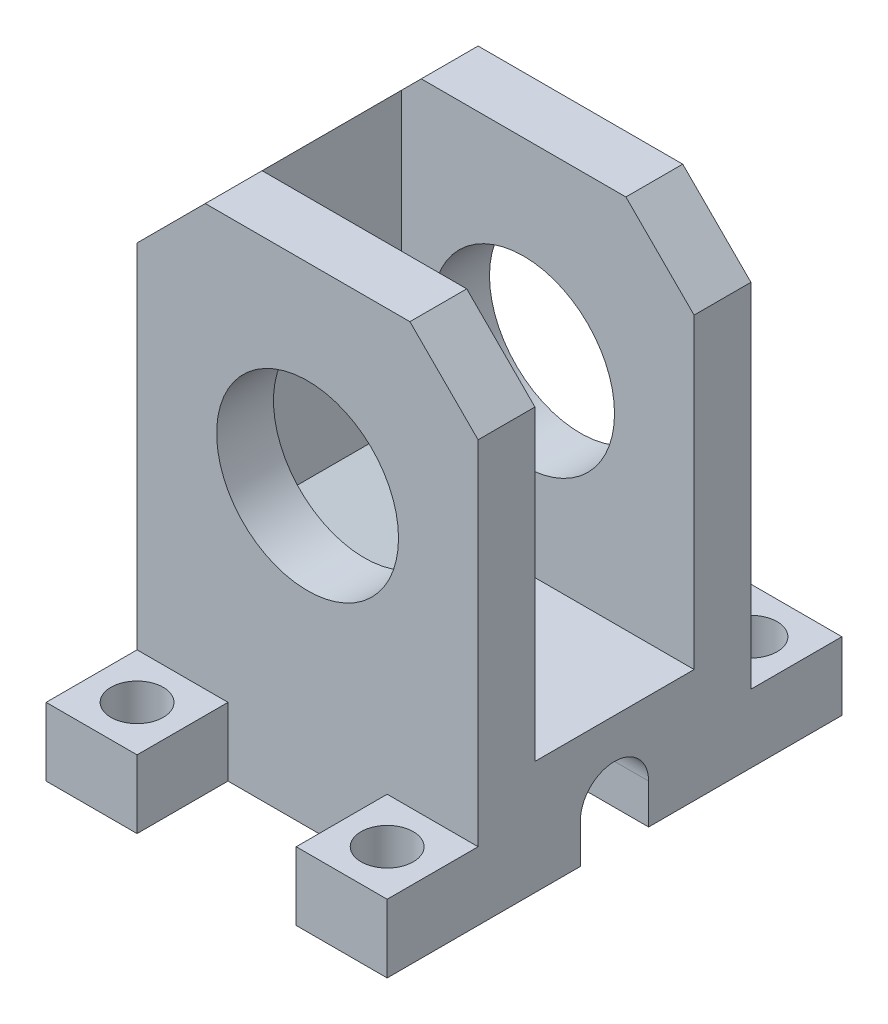
SolidWorks part; units mm, degrees
ref_plane "Plan de face" through (0, 0, 0) normal (0, 0, 1) x (1, 0, 0)
ref_plane "Plan de dessus" through (0, 0, 0) normal (0, 1, 0) x (1, 0, 0)
ref_plane "Plan de droite" through (0, 0, 0) normal (1, 0, 0) x (0, 0, -1)
sketch "Esquisse1" plane through (0, 0, 0) normal (0, 0, 1) x (1, 0, 0)
  line L0 (0, 0) -> (15, 0)
  line L1 (0, 0) -> (-15, 0)
  line L2 (-15, 0) -> (-15, 45)
  line L3 (-15, 45) -> (15, 45)
  line L4 (15, 45) -> (15, 0)
  line L5 (0, 0) -> (0, 28) construction
  circle A0 centre (0, 28) radius 8
  dimension "D1" = 28
extrude "Boss.-Extru.1" add sketch "Esquisse1" against normal blind 5
sketch "Esquisse2" plane through (0, 0, -5) normal (0, 0, -1) x (-1, 0, 0)
  line L0 (-15, 0) -> (15, 0)
  line L1 (15, 0) -> (15, 12)
  line L2 (15, 45) -> (15, 0) construction
  line L3 (15, 12) -> (-15, 12)
  line L4 (-15, 0) -> (-15, 45) construction
  line L5 (-15, 12) -> (-15, 0)
extrude "Boss.-Extru.2" add sketch "Esquisse2" along normal blind 14
sketch "Esquisse4" plane through (0, 0, 0) normal (0, -1, 0) x (1, 0, 0)
  line L0 (-15, -19) -> (15, -19)
  line L1 (15, -19) -> (15, -24)
  line L2 (15, -24) -> (-15, -24)
  line L3 (-15, -24) -> (-15, -19)
extrude "Boss.-Extru.3" add sketch "Esquisse4" against normal blind 45
sketch "Esquisse6" plane through (0, 0, -24) normal (0, 0, -1) x (-1, 0, 0)
  line L0 (0, 0) -> (0, 28) construction
  circle A1 centre (0, 28) radius 8
extrude "Enlèv. mat.-Extru.3" cut sketch "Esquisse6" against normal blind 10
sketch "Esquisse8" plane through (0, 0, 0) normal (0, -1, 0) x (1, 0, 0)
  line L0 (-15, 0) -> (-15, 8)
  line L1 (-15, 8) -> (-7, 8)
  line L2 (-7, 8) -> (-7, 0)
  line L3 (-15, 0) -> (15, 0) construction
  line L4 (-15, 0) -> (-7, 0)
  line L5 (15, 0) -> (15, 8)
  line L6 (15, 8) -> (7, 8)
  line L7 (7, 8) -> (7, 0)
  line L8 (7, 0) -> (15, 0)
  line L9 (-15, -24) -> (-15, -32)
  line L10 (-15, -32) -> (-7, -32)
  line L11 (-7, -32) -> (-7, -24)
  line L12 (-15, -24) -> (15, -24) construction
  line L13 (-7, -24) -> (-15, -24)
  line L14 (15, -24) -> (15, -32)
  line L15 (15, -32) -> (7, -32)
  line L16 (7, -32) -> (7, -24)
  line L17 (7, -24) -> (15, -24)
  line L18 (15, -32) -> (7, -24) construction
  line L19 (7, -32) -> (15, -24) construction
  line L20 (7, 8) -> (15, 0) construction
  line L21 (7, 0) -> (15, 8) construction
  line L22 (-15, 8) -> (-7, 0) construction
  line L23 (-7, 8) -> (-15, 0) construction
  line L24 (-15, -24) -> (-7, -32) construction
  line L25 (-15, -32) -> (-7, -24) construction
  circle A0 centre (-11, 4) radius 2.3
  circle A2 centre (11, -28) radius 2.3
  circle A3 centre (-11, -28) radius 2.3
  circle A4 centre (11, 4) radius 2.3
extrude "Boss.-Extru.4" add sketch "Esquisse8" against normal blind 8
sketch "Esquisse9" plane through (0, 0, 0) normal (0, -1, 0) x (1, 0, 0)
  line L0 (-15, 8) -> (-15, -32)
  line L1 (-15, -32) -> (-7, -32)
  line L2 (-7, -32) -> (-7, -24)
  line L3 (-7, -24) -> (7, -24)
  line L4 (7, -24) -> (7, -32)
  line L5 (7, -32) -> (15, -32)
  line L6 (15, -32) -> (15, 8)
  line L7 (15, 8) -> (7, 8)
  line L8 (7, 8) -> (7, 0) construction
  line L9 (15, 8) -> (7, 8) construction
  line L10 (7, 8) -> (7, 0)
  line L11 (7, 0) -> (-7, 0)
  line L12 (-7, 0) -> (-7, 8)
  line L13 (-7, 8) -> (-15, 8)
extrude "Enlèv. mat.-Extru.4" cut sketch "Esquisse9" against normal blind 2
sketch "Esquisse10" plane through (-15, 0, 0) normal (-1, 0, 0) x (0, 0, 1)
  line L0 (-12, 2) -> (-12, 5.5) construction
  line L1 (8, 2) -> (-32, 2) construction
  line L2 (-15, 5.5) -> (-15, 2)
  line L3 (-15, 2) -> (-9, 2)
  line L4 (-9, 2) -> (-9, 5.5)
  circle A0 centre (-12, 5.5) radius 3
extrude "Enlèv. mat.-Extru.5" cut sketch "Esquisse10" against normal blind 50
sketch "Esquisse11" plane through (0, 0, 0) normal (0, 0, 1) x (1, 0, 0)
  line L0 (-15, 45) -> (-15, 39)
  line L1 (-15, 45) -> (-15, 8) construction
  line L2 (-15, 45) -> (-9, 45)
  line L3 (15, 45) -> (-15, 45) construction
  line L4 (-9, 45) -> (-15, 39)
  line L5 (15, 45) -> (9, 45)
  line L6 (9, 45) -> (15, 45)
  line L7 (15, 45) -> (15, 39)
  line L8 (15, 8) -> (15, 45) construction
  line L9 (15, 39) -> (9, 45)
  line M8 (15, 8) -> (15, 45)
  line M9 (15, 45) -> (-15, 45)
  line M10 (-15, 45) -> (-15, 8)
extrude "Enlèv. mat.-Extru.6" cut sketch "Esquisse11" against normal blind 50 contours L4 M9 M10 | L9 M8 M9
sketch "Esquisse12" plane through (0, 0, -5) normal (0, 0, -1) x (-1, 0, 0)
  line L0 (0, 20) -> (0, 12) construction
  line L1 (0, 12) -> (15, 12)
  line L2 (15, 39) -> (15, 8) construction
  line L3 (15, 12) -> (15, 20)
  line L4 (15, 20) -> (0, 12)
  circle A0 centre (0, 28) radius 8 construction
extrude "Boss.-Extru.5" add sketch "Esquisse12" along normal blind 14
sketch "Esquisse13" plane through (0, 0, -19) normal (0, 0, 1) x (1, 0, 0)
  line L0 (-15, 20) -> (-15, 39)
  line L15 (-15, 39) -> (-10.7574, 43.2426)
  line L16 (-9, 45) -> (-15, 39) construction
  line L17 (-10.7574, 43.2426) -> (-10.7574, 17.084)
  line L18 (-15, 20) -> (-10.7574, 17.084)
extrude "Boss.-Extru.7" add sketch "Esquisse13" along normal blind 15
